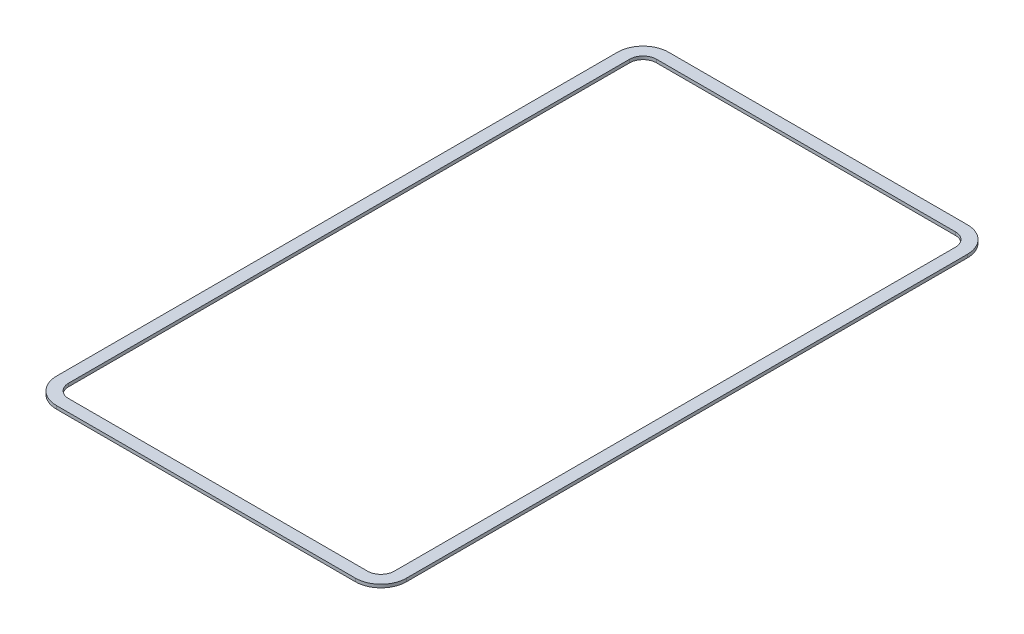
SolidWorks part; units mm, degrees
ref_plane "Front Plane" through (0, 0, 0) normal (0, 0, 1) x (1, 0, 0)
ref_plane "Top Plane" through (0, 0, 0) normal (0, 1, 0) x (1, 0, 0)
ref_plane "Right Plane" through (0, 0, 0) normal (1, 0, 0) x (0, 0, -1)
sketch "Sketch1" plane through (0, 0, 0) normal (0, 1, 0) x (1, 0, 0)
  line L1 (-129.2062, 75.5043) -> (-82.3199, 75.5043)
  line L2 (-133.2062, 71.5043) -> (-133.2062, -16.4957)
  line L3 (-129.2062, -20.4957) -> (-82.3199, -20.4957)
  line L4 (-78.3199, 71.5043) -> (-78.3199, -16.4957)
  line L5 (-131.3062, 71.5043) -> (-131.3062, -16.4957)
  line L6 (-129.2062, -18.5957) -> (-82.3199, -18.5957)
  line L7 (-80.2199, 71.5043) -> (-80.2199, -16.4957)
  line L8 (-129.2062, 73.6043) -> (-82.3199, 73.6043)
  arc A0 (-133.2062, -16.4957) -> (-129.2062, -20.4957) centre (-129.2062, -16.4957) ccw
  arc A1 (-82.3199, -20.4957) -> (-78.3199, -16.4957) centre (-82.3199, -16.4957) ccw
  arc A2 (-82.3199, 75.5043) -> (-78.3199, 71.5043) centre (-82.3199, 71.5043) cw
  arc A3 (-129.2062, 75.5043) -> (-133.2062, 71.5043) centre (-129.2062, 71.5043) ccw
  arc A4 (-131.3062, -16.4957) -> (-129.2062, -18.5957) centre (-129.2062, -16.4957) ccw
  arc A5 (-82.3199, -18.5957) -> (-80.2199, -16.4957) centre (-82.3199, -16.4957) ccw
  arc A6 (-82.3199, 73.6043) -> (-80.2199, 71.5043) centre (-82.3199, 71.5043) cw
  arc A7 (-129.2062, 73.6043) -> (-131.3062, 71.5043) centre (-129.2062, 71.5043) ccw
  point P2 (-109.0227, 27.5043)
extrude "Boss-Extrude1" add sketch "Sketch1" along normal blind 0.5
